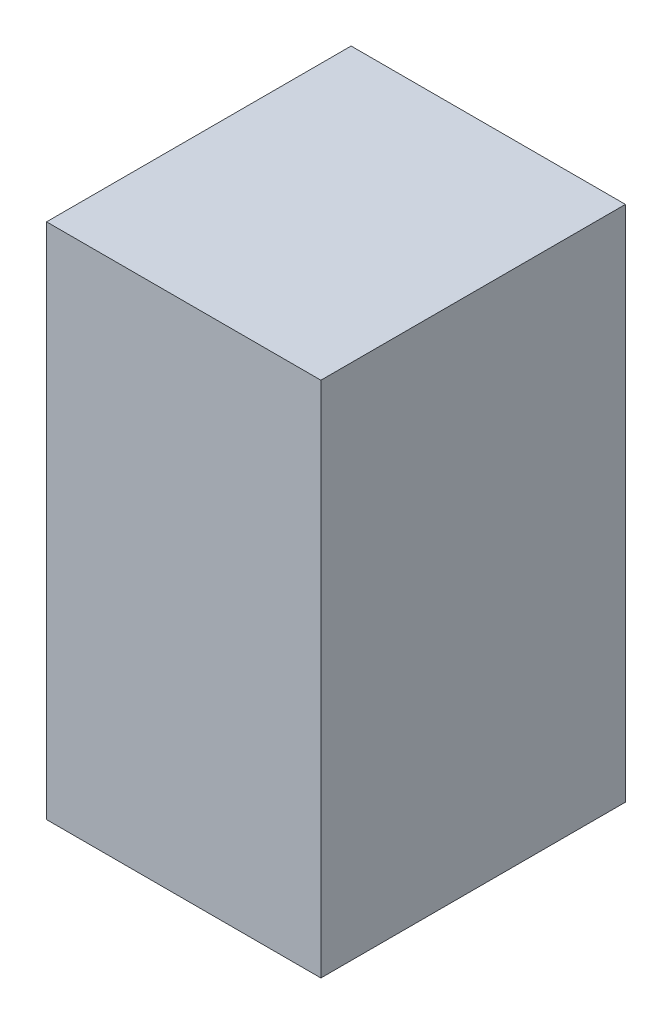
SolidWorks part; units mm, degrees
ref_plane "Front Plane" through (0, 0, 0) normal (0, 0, 1) x (1, 0, 0)
ref_plane "Top Plane" through (0, 0, 0) normal (0, 1, 0) x (1, 0, 0)
ref_plane "Right Plane" through (0, 0, 0) normal (1, 0, 0) x (0, 0, -1)
sketch "Sketch1" plane through (0, 0, 0) normal (0, 0, 1) x (1, 0, 0)
  line L0 (-0.4508, 0.85) -> (0.45, 0.85)
  line L1 (0.45, 0.85) -> (0.45, -0.85)
  line L2 (0.45, -0.85) -> (-0.4508, -0.85)
  line L3 (-0.4508, -0.85) -> (-0.4508, 0.85)
extrude "Component_Outline" add sketch "Sketch1" along normal blind 1 separate body
sketch3d "3DSketch1"
  line L0 (0, 0, 0) -> (1, 0, 0)
  line L1 (0, 0, 0) -> (0, 1, 0)
  line L2 (0, 0, 0) -> (0, 0, 1)
  point P0 (0, 0, 0)
